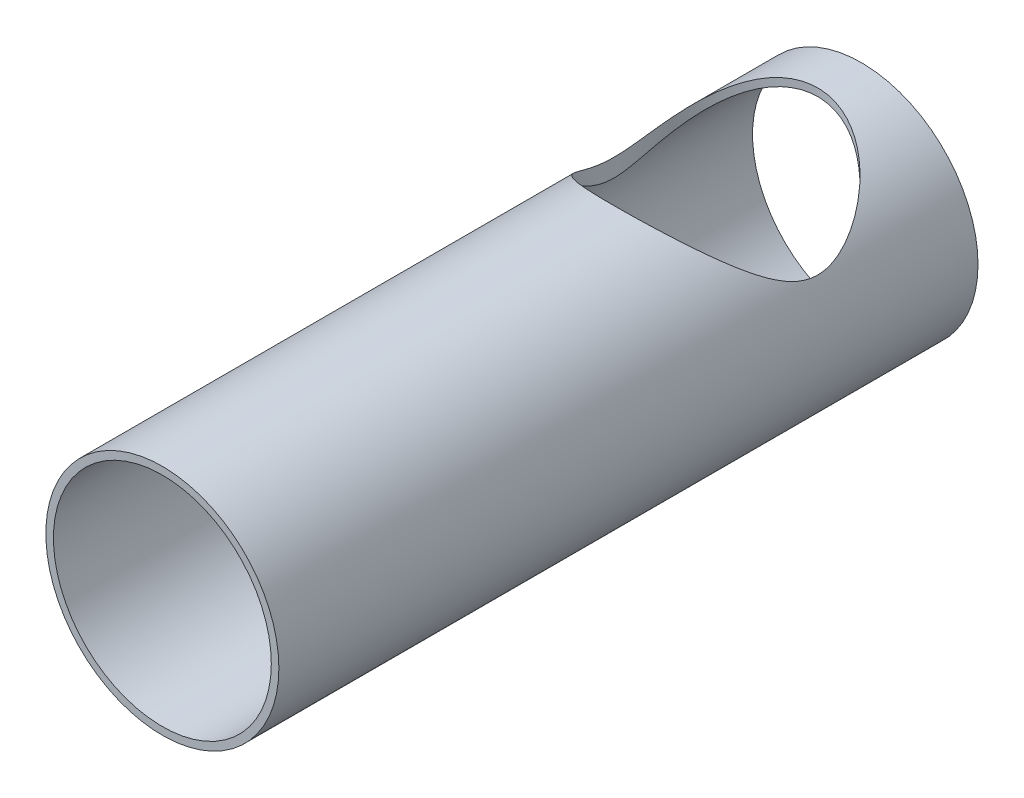
SolidWorks part; units mm, degrees
material "2024-T3"
ref_plane "Front Plane" through (0, 0, 0) normal (0, 0, 1) x (1, 0, 0)
ref_plane "Top Plane" through (0, 0, 0) normal (0, 1, 0) x (1, 0, 0)
ref_plane "Right Plane" through (0, 0, 0) normal (1, 0, 0) x (0, 0, -1)
sketch "Sketch1" plane through (0, 0, 0) normal (0, 0, 1) x (1, 0, 0)
  circle A0 centre (0, 0) radius 23.749
  circle A1 centre (0, 0) radius 25.4
  dimension "D1" = 50.8
  dimension "D2" = 47.498
extrude "Boss-Extrude1" add sketch "Sketch1" along normal blind 152.4
ref_plane "Plane1" through (0, 25.4, 0) normal (0, 1, 0) x (-1, 0, 0)
sketch "Sketch2" plane through (0, 25.4, 0) normal (0, 1, 0) x (-1, 0, 0)
  line L1 (-25.4, 0) -> (25.4, 0) construction
  circle A0 centre (0, 31.75) radius 22.225
  dimension "D1" = 44.45
  dimension "D2" = 31.75
extrude "Cut-Extrude2" cut sketch "Sketch2" against normal blind 22.86
